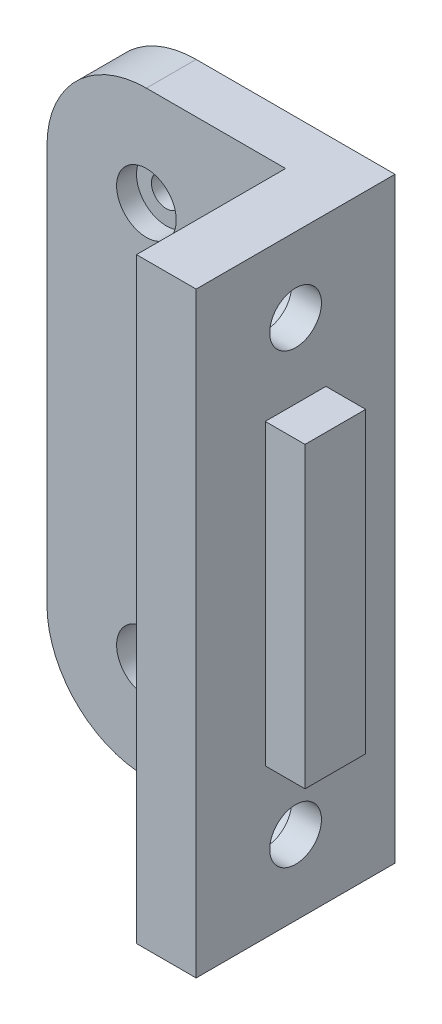
SolidWorks part; units mm, degrees
ref_plane "前视基准面" through (0, 0, 0) normal (0, 0, 1) x (1, 0, 0)
ref_plane "上视基准面" through (0, 0, 0) normal (0, 1, 0) x (1, 0, 0)
ref_plane "右视基准面" through (0, 0, 0) normal (1, 0, 0) x (0, 0, -1)
other "Configuration Table"
sketch "草图1" plane through (0, 0, 0) normal (0, 1, 0) x (1, 0, 0)
  line L1 (0, 0) -> (20, 0)
  line L2 (0, 0) -> (0, -20)
  line L3 (0, -20) -> (20, -20)
  line L4 (20, 0) -> (20, -20)
extrude "凸台-拉伸1" add sketch "草图1" along normal blind 90
sketch "草图2" plane through (0, 0, 0) normal (0, 0, -1) x (-1, 0, 0)
  line L1 (0, 90) -> (20, 90)
  line L2 (0, 90) -> (0, 0)
  line L3 (0, 0) -> (20, 0)
  line L4 (20, 90) -> (20, 0)
extrude "凸台-拉伸2" add sketch "草图2" against normal blind 20
sketch "草图4" plane through (0, 0, 20) normal (0, 0, 1) x (1, 0, 0)
  line L0 (-20, 0) -> (20, 0) construction
  line L1 (-20, 90) -> (14, 90)
  line L2 (-20, 90) -> (-20, 0)
  line L3 (-20, 0) -> (14, 0)
  line L4 (14, 90) -> (14, 0)
extrude "切除-拉伸1" cut sketch "草图4" against normal blind 15
sketch "草图6" plane through (20, 0, 0) normal (1, 0, 0) x (0, 0, -1)
  line L1 (-20, 90) -> (0, 90) construction
  line L2 (-20, 0) -> (0, 0) construction
  line L3 (-10, 45) -> (-10, 0)
  line L4 (-10, 45) -> (-10, 90)
  circle A0 centre (-10, 67.5) radius 2.6
  circle A1 centre (-10, 22.5) radius 2.6
extrude "切除-拉伸2" cut sketch "草图6" against normal blind 15 contours L4 A0 | L4 A0 | L3 A1 | L3 A1
sketch "草图8" plane through (14, 0, 0) normal (-1, 0, 0) x (0, 0, 1)
  circle A0 centre (10, 67.5) radius 5
  circle A1 centre (10, 22.5) radius 5
extrude "切除-拉伸3" cut sketch "草图8" against normal blind 3
sketch "草图9" plane through (0, 0, 5) normal (0, 0, 1) x (1, 0, 0)
  line L0 (20, 45) -> (20, 65)
  line L1 (20, 90) -> (20, 0) construction
  line L2 (20, 45) -> (20, 25)
  line L3 (20, 65) -> (10, 65)
  line L4 (20, 25) -> (10, 25)
  line L5 (10, 65) -> (0, 65)
  line L7 (10, 25) -> (0, 25)
  circle A0 centre (10, 65) radius 1.5
  circle A1 centre (10, 25) radius 1.5
  circle A2 centre (0, 65) radius 1.5
  circle A3 centre (0, 25) radius 1.5
extrude "切除-拉伸4" cut sketch "草图9" against normal blind 5
sketch "草图10" plane through (0, 0, 0) normal (0, 0, -1) x (-1, 0, 0)
  line L4 (0, 15) -> (-20, 15)
  line L5 (-20, 90) -> (-20, 0) construction
  line L6 (-20, 15) -> (-20, 0)
  line L7 (-20, 0) -> (20, 0)
  line L8 (20, 0) -> (20, 90)
  line L9 (20, 90) -> (-20, 90)
  line L10 (-20, 90) -> (-20, 75)
  line L11 (-20, 75) -> (0, 75)
  line L12 (10, 65) -> (10, 25)
  arc A0 (0, 75) -> (10, 65) centre (0, 65) cw
  arc A1 (0, 15) -> (10, 25) centre (0, 25) ccw
extrude "切除-拉伸5" cut sketch "草图10" against normal blind 40
sketch "草图11" plane through (20, 0, 0) normal (1, 0, 0) x (0, 0, -1)
  line L0 (-10, 67.5) -> (-10, 60)
  line L1 (-10, 22.5) -> (-10, 30)
  line L2 (-10, 60) -> (-6.95, 60)
  line L3 (-10, 30) -> (-13.05, 30)
  line L5 (-13.05, 30) -> (-6.95, 30)
  line L6 (-13.05, 30) -> (-13.05, 60)
  line L7 (-13.05, 60) -> (-6.95, 60)
  line L8 (-6.95, 30) -> (-6.95, 60)
extrude "凸台-拉伸3" add sketch "草图11" along normal blind 4 contours L5 L8 L2 L7 L6 L3
sketch "草图12" plane through (0, 0, 5) normal (0, 0, 1) x (1, 0, 0)
  circle A0 centre (0, 65) radius 3
  circle A1 centre (10, 65) radius 3
  circle A2 centre (0, 25) radius 3
  circle A3 centre (10, 25) radius 3
extrude "切除-拉伸6" cut sketch "草图12" against normal blind 2
